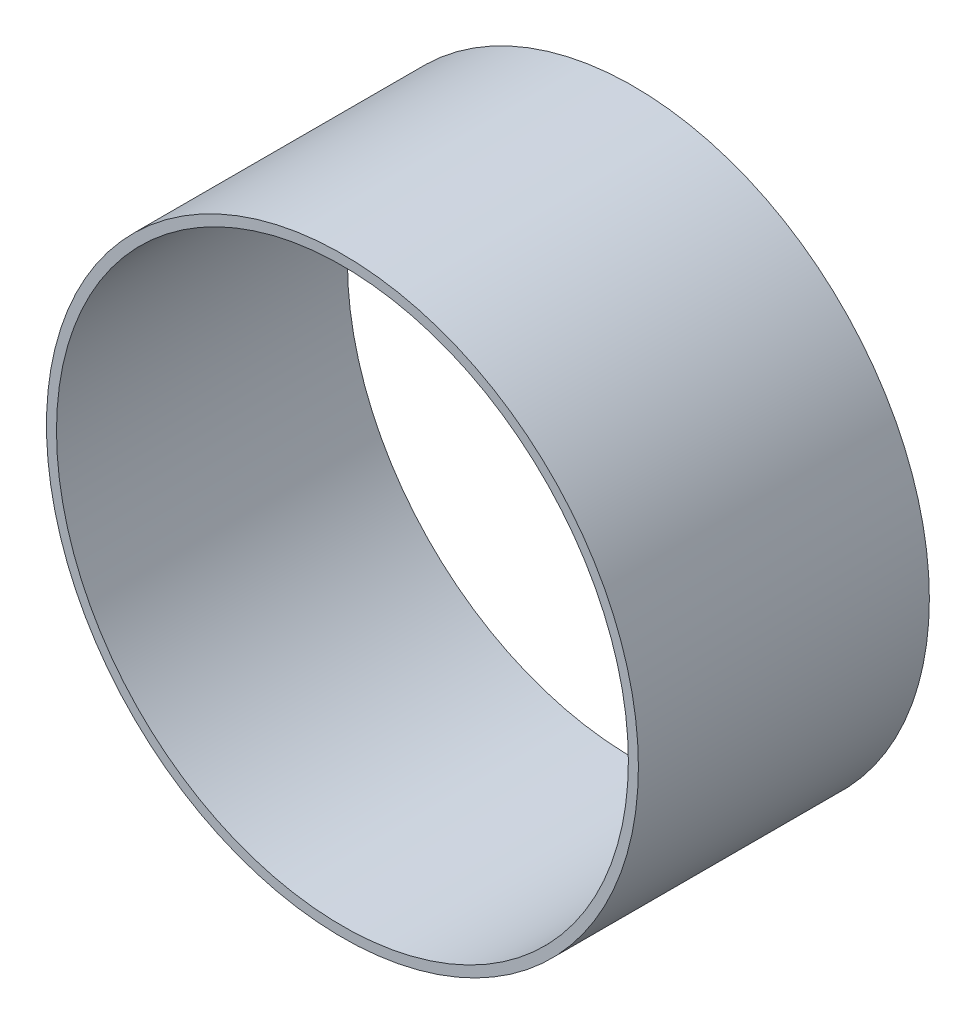
SolidWorks part; units mm, degrees
ref_plane "Спереди" through (0, 0, 0) normal (0, 0, 1) x (1, 0, 0)
ref_plane "Сверху" through (0, 0, 0) normal (0, 1, 0) x (1, 0, 0)
ref_plane "Справа" through (0, 0, 0) normal (1, 0, 0) x (0, 0, -1)
sketch "Эскиз1" plane through (0, 0, 0) normal (0, 0, 1) x (1, 0, 0)
  circle A0 centre (0, 0) radius 88.5
  circle A1 centre (0, 0) radius 85.5
extrude "Rim_reference" add sketch "Эскиз1" along normal blind 87 from offset 39.5
